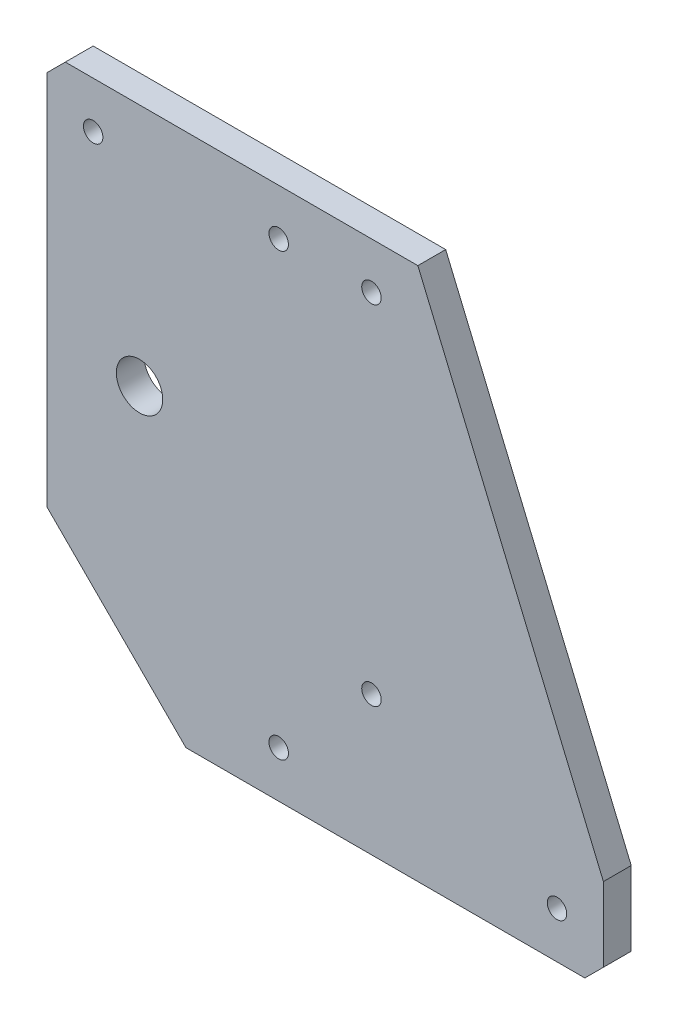
SolidWorks part; units mm, degrees
ref_plane "前视基准面" through (0, 0, 0) normal (0, 0, 1) x (1, 0, 0)
ref_plane "上视基准面" through (0, 0, 0) normal (0, 1, 0) x (1, 0, 0)
ref_plane "右视基准面" through (0, 0, 0) normal (1, 0, 0) x (0, 0, -1)
sketch "草图1" plane through (0, 0, 0) normal (0, 0, 1) x (1, 0, 0)
  line L0 (-20, 52.5) -> (-20, -62.5)
  line L1 (-20, -62.5) -> (100, -62.5)
  line L2 (100, -62.5) -> (100, -42.5)
  line L3 (100, -42.5) -> (60, 52.5)
  line L4 (60, 52.5) -> (-20, 52.5)
  circle A0 centre (0, 0) radius 5
  dimension "D1" = 62.5
  dimension "D2" = 10
  dimension "D3" = 52.5
  dimension "D4" = 20
  dimension "D5" = 20
  dimension "D6" = 80
  dimension "D7" = 40
extrude "凸台-拉伸1" add sketch "草图1" along normal mid plane 6
sketch "草图2" plane through (0, 0, 3) normal (0, 0, 1) x (1, 0, 0)
  line L0 (60, 52.5) -> (-20, 52.5) construction
  line L1 (-20, 52.5) -> (-20, -62.5) construction
  line L2 (50, 42.5) -> (50, -32.5) construction
  line L3 (30, -52.5) -> (90, -52.5) construction
  line L4 (-20, -62.5) -> (100, -62.5) construction
  line L5 (100, -62.5) -> (100, -42.5) construction
  circle A0 centre (-10, 42.5) radius 2.1
  circle A1 centre (30, 42.5) radius 2.1
  circle A2 centre (50, 42.5) radius 2.1
  circle A3 centre (50, -32.5) radius 2.1
  circle A4 centre (30, -52.5) radius 2.1
  circle A5 centre (90, -52.5) radius 2.1
  dimension "D1" = 4.2
  dimension "D2" = 10
  dimension "D3" = 10
  dimension "D4" = 40
  dimension "D5" = 10
  dimension "D8" = 10
  dimension "D9" = 20
  dimension "D6" = 10
  dimension "D7" = 20
extrude "切除-拉伸1" cut sketch "草图2" against normal through all
chamfer "倒角1" distance 30 angle 45 1 edges at (-20, -62.5, 0)
chamfer "倒角3" distance 4 angle 45 2 edges at (-20, 52.5, 0) (100, -62.5, 0)
chamfer "倒角2" distance 2 angle 45 4 edges at (92.1, -52.5, -3) (32.1, -52.5, -3) (52.1, -32.5, -3) (52.1, 42.5, -3)
